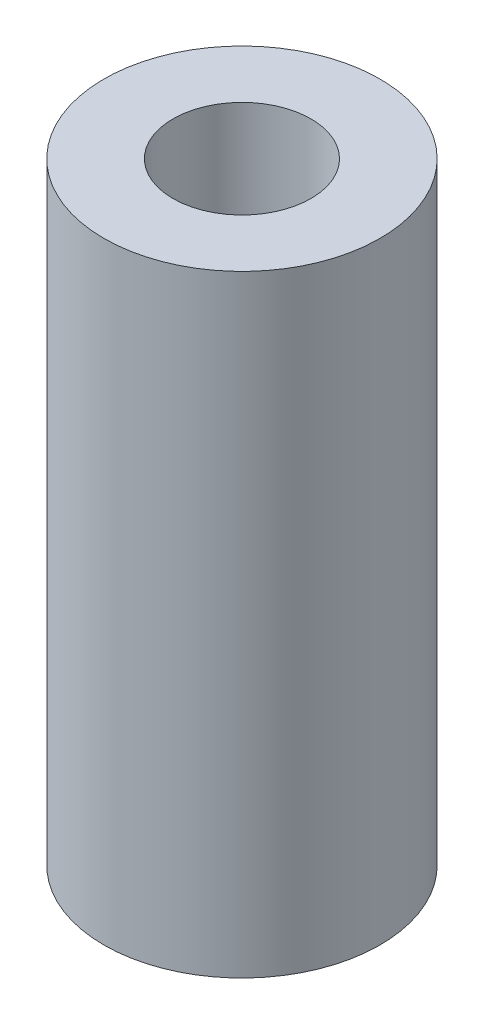
SolidWorks part; units mm, degrees
ref_plane "Front Plane" through (0, 0, 0) normal (0, 0, 1) x (1, 0, 0)
ref_plane "Top Plane" through (0, 0, 0) normal (0, 1, 0) x (1, 0, 0)
ref_plane "Right Plane" through (0, 0, 0) normal (1, 0, 0) x (0, 0, -1)
sketch "Sketch1" plane through (0, 0, 0) normal (0, 1, 0) x (1, 0, 0)
  circle A0 centre (0, 0) radius 4.5
  circle A1 centre (0, 0) radius 2.25
  dimension "D1" = 9
  dimension "D2" = 4.5
extrude "Boss-Extrude1" add sketch "Sketch1" along normal blind 19.95
